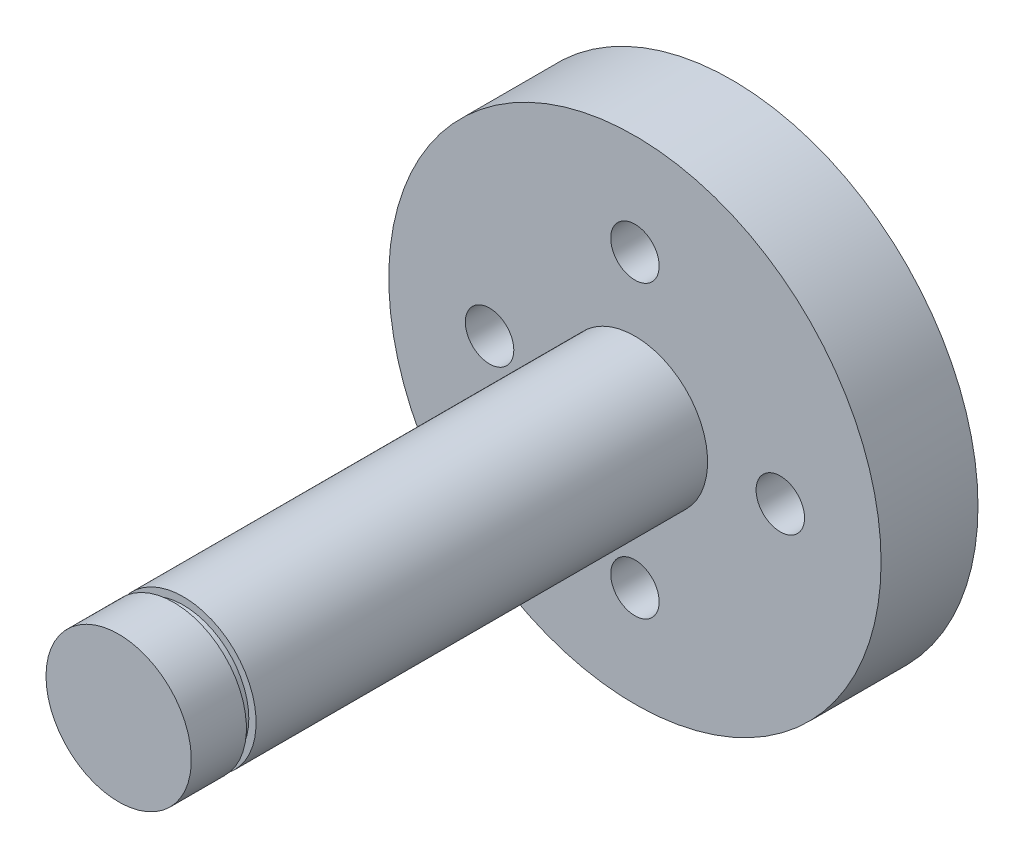
SolidWorks part; units mm, degrees
ref_plane "Alzado" through (0, 0, 0) normal (0, 0, 1) x (1, 0, 0)
ref_plane "Planta" through (0, 0, 0) normal (0, 1, 0) x (1, 0, 0)
ref_plane "Vista lateral" through (0, 0, 0) normal (1, 0, 0) x (0, 0, -1)
sketch "Sketch1" plane through (0, 0, 0) normal (0, 0, 1) x (1, 0, 0)
  circle A0 centre (0, 0) radius 25.4
  dimension "D1" = 50.8
extrude "Boss-Extrude1" add sketch "Sketch1" along normal blind 10
sketch "Sketch3" plane through (0, 0, 10) normal (0, 0, 1) x (1, 0, 0)
  circle A0 centre (0, 0) radius 7.5
  dimension "D1" = 15
sketch "Sketch4" plane through (0, 0, 10) normal (0, 0, 1) x (1, 0, 0)
  circle A0 centre (0, 0) radius 15 construction
  dimension "D1" = 30
hole_wizard "Tap Drill for M6x1.0 Tap1" positions "Sketch5" profile "Sketch6" hole size "M6x1.0" standard "ANSI Metric" end condition through all
sketch "Sketch5" plane through (0, 0, 10) normal (0, 0, 1) x (1, 0, 0)
  circle A0 centre (0, 0) radius 15 construction
  point P0 (0, 15)
sketch "Sketch6" plane through (0, 15, 10) normal (1, 0, 0) x (0, -1, 0)
  line L0 (0, 0) -> (0, 10)
  line L1 (0, 10) -> (2.5, 10)
  line L2 (2.5, 10) -> (2.5, 0)
  line L5 (2.5, 0) -> (0, 0)
  line L11 (0, -6.35) -> (0, 107.95) construction
  dimension "Thru Hole Dia." = 5
  dimension "Thru Hole Depth" = 10
pattern_circular "CirPattern1" count 4 over 360 about axis through (0, 0, 0) along (0, 0, 1) of "Tap Drill for M6x1.0 Tap1"
extrude "Boss-Extrude2" add sketch "Sketch3" along normal blind 53.27 contours A0
sketch "Sketch7" plane through (0, 0, 63.27) normal (0, 0, 1) x (1, 0, 0)
  circle A0 centre (0, 0) radius 7.5
  dimension "D1" = 15
sketch "Sketch11" [suppressed] plane through (0, 0, 0) normal (1, 0, 0) x (0, 0, -1)
  line L0 (0, 7.5) -> (-76.2, 7.5) construction
  line L1 (-89.6, 0) -> (0, 0) construction
  line L2 (-76.7, 6.9) -> (-75.7, 6.9)
  line L3 (-76.7, 6.9) -> (-76.7, 8.1)
  line L4 (-76.7, 8.1) -> (-75.7, 8.1)
  line L5 (-75.7, 6.9) -> (-75.7, 8.1)
  line L6 (-76.7, 6.9) -> (-75.7, 8.1) construction
  line L7 (-76.7, 8.1) -> (-75.7, 6.9) construction
  line L8 (-10, 25.4) -> (-10, -25.4) construction
  line L11 (-89.6, 7.5) -> (-89.6, -7.5) construction
  line L13 (-89.6, -7.5) -> (-10, -7.5) construction
  dimension "D1" = 1
  dimension "D2" = 0.6
  dimension "D3" = 65.7
  dimension "D4" = 15
revolve "Cut-Revolve1" [suppressed] cut sketch "Sketch11" angle 360 about L1
sketch "Sketch12" plane through (0, 0, 0) normal (0, 1, 0) x (1, 0, 0)
  line L0 (-7.5, -10) -> (-7.5, -63.27) construction
  line L1 (-8.25, -57.59) -> (-6.75, -57.59)
  line L2 (-8.25, -57.59) -> (-8.25, -56.59)
  line L3 (-8.25, -56.59) -> (-6.75, -56.59)
  line L4 (-6.75, -57.59) -> (-6.75, -56.59)
  line L5 (-8.25, -57.59) -> (-6.75, -56.59) construction
  line L6 (-8.25, -56.59) -> (-6.75, -57.59) construction
  line L8 (0, -63.27) -> (0, -10) construction
  line L9 (0, -63.27) -> (0, -10) construction
  line L10 (0, -10) -> (0, 0) construction
  line L11 (-7.5, -63.27) -> (7.5, -63.27) construction
  line L12 (-7.5, -10) -> (7.5, -10) construction
  point P0 (-7.5, -57.09)
  dimension "D1" = 46.59
  dimension "D2" = 1
  dimension "D3" = 1.5
revolve "Cut-Revolve2" cut sketch "Sketch12" angle 360 about L9
sketch "Sketch9" [suppressed] plane through (0, 0, 89.6) normal (0, 0, 1) x (1, 0, 0)
  line L1 (-2.5, 5) -> (2.5, 5)
  line L2 (-2.5, 5) -> (-2.5, 10)
  line L3 (-2.5, 10) -> (2.5, 10)
  line L4 (2.5, 5) -> (2.5, 10)
  line L5 (-2.5, 5) -> (2.5, 10) construction
  line L6 (-2.5, 10) -> (2.5, 5) construction
  circle A0 centre (0, 0) radius 7.5 construction
  point P0 (0, 7.5)
  dimension "D1" = 5
extrude "Cut-Extrude3" [suppressed] cut sketch "Sketch9" against normal blind 40.2
pattern_linear "LPattern2" [suppressed] count 2 spacing 7.7
pattern_linear "LPattern3" [suppressed] count 2 spacing 12.7
